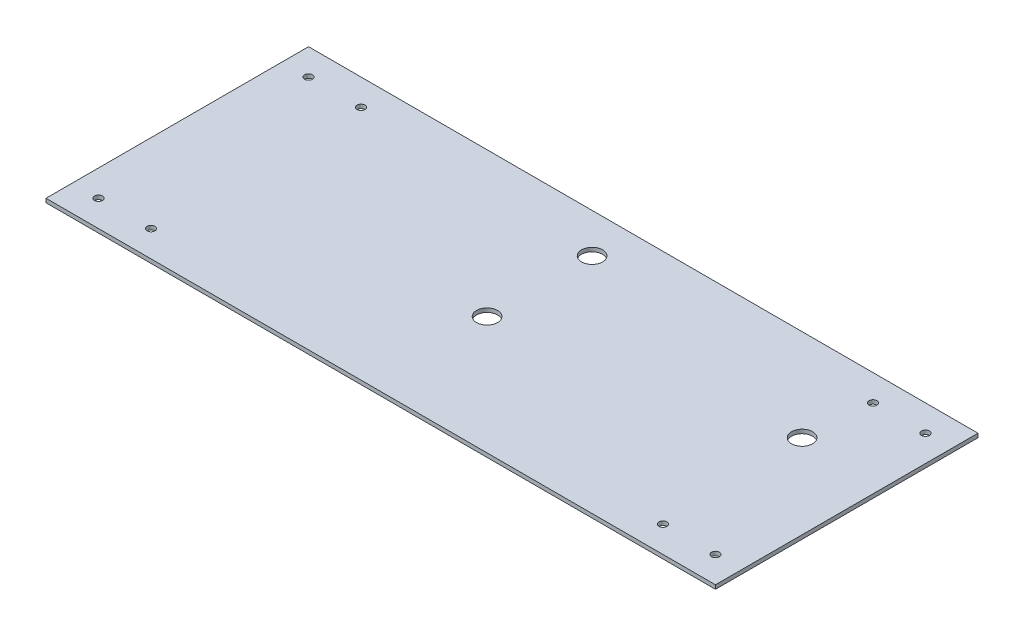
SolidWorks part; units mm, degrees
ref_plane "Front Plane" through (0, 0, 0) normal (0, 0, 1) x (1, 0, 0)
ref_plane "Top Plane" through (0, 0, 0) normal (0, 1, 0) x (1, 0, 0)
ref_plane "Right Plane" through (0, 0, 0) normal (1, 0, 0) x (0, 0, -1)
sketch "Sketch1" plane through (0, 0, 0) normal (0, 1, 0) x (1, 0, 0)
  line L1 (-127.5, -50) -> (127.5, -50)
  line L2 (-127.5, -50) -> (-127.5, 50)
  line L3 (-127.5, 50) -> (127.5, 50)
  line L4 (127.5, -50) -> (127.5, 50)
  line L5 (-127.5, -50) -> (127.5, 50) construction
  line L6 (-127.5, 50) -> (127.5, -50) construction
  point P0 (0, 0)
  dimension "D1" = 100
  dimension "D2" = 255
extrude "Boss-Extrude1" add sketch "Sketch1" along normal blind 1.5
sketch "Sketch2" plane through (0, 1.5, 0) normal (0, 1, 0) x (1, 0, 0)
  line L0 (127.5, -50) -> (127.5, 50) construction
  line L1 (127.5, 50) -> (-127.5, 50) construction
  line L2 (-127.5, -50) -> (127.5, -50) construction
  line L3 (-127.5, 50) -> (-127.5, -50) construction
  circle A0 centre (117.5, 40) radius 1.5
  circle A1 centre (97.5, 40) radius 1.5
  circle A2 centre (97.5, -40) radius 1.5
  circle A3 centre (117.5, -40) radius 1.5
  circle A4 centre (-97.5, 40) radius 1.5
  circle A5 centre (-117.5, 40) radius 1.5
  circle A6 centre (-117.5, -40) radius 1.5
  circle A7 centre (-97.5, -40) radius 1.5
  dimension "D1" = 3
  dimension "D2" = 10
  dimension "D3" = 10
  dimension "D6" = 10
  dimension "D7" = 20
  dimension "D9" = 10
  dimension "D4" = 2
  dimension "D5" = 2
  dimension "D8" = 2
extrude "Cut-Extrude2" cut sketch "Sketch2" against normal blind 10
sketch "Sketch4" plane through (0, 1.5, 0) normal (0, 1, 0) x (1, 0, 0)
  line L0 (127.5, -50) -> (127.5, 50) construction
  line L1 (127.5, 50) -> (-127.5, 50) construction
  circle A0 centre (95.5, 15) radius 4
  circle A1 centre (-4.5, 35) radius 4
  circle A2 centre (-4.5, -5) radius 4
  dimension "D1" = 8
  dimension "D2" = 32
  dimension "D3" = 35
  dimension "D4" = 15
  dimension "D5" = 40
  dimension "D6" = 100
extrude "Cut-Extrude3" cut sketch "Sketch4" against normal through all
